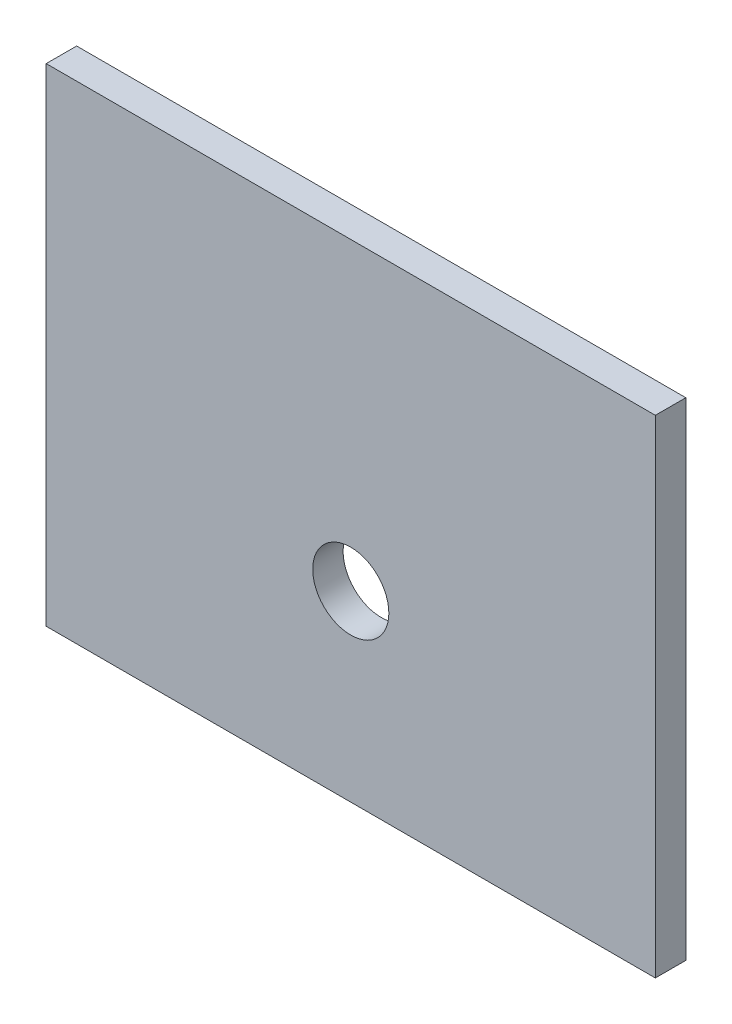
SolidWorks part; units mm, degrees
ref_plane "Front Plane" through (0, 0, 0) normal (0, 0, 1) x (1, 0, 0)
ref_plane "Top Plane" through (0, 0, 0) normal (0, 1, 0) x (1, 0, 0)
ref_plane "Right Plane" through (0, 0, 0) normal (1, 0, 0) x (0, 0, -1)
sketch "Sketch1" plane through (0, 0, 0) normal (0, 0, 1) x (1, 0, 0)
  line L1 (-31.75, 25.4) -> (31.75, 25.4)
  line L2 (-31.75, 25.4) -> (-31.75, -25.4)
  line L3 (-31.75, -25.4) -> (31.75, -25.4)
  line L4 (31.75, 25.4) -> (31.75, -25.4)
  line L5 (-31.75, 25.4) -> (31.75, -25.4) construction
  line L6 (-31.75, -25.4) -> (31.75, 25.4) construction
  circle A0 centre (0, -6.35) radius 3.9688
  point P0 (0, 0)
  dimension "D3" = 19.05
  dimension "D1" = 50.8
  dimension "D2" = 63.5
extrude "Boss-Extrude1" add sketch "Sketch1" along normal blind 3.175
sketch "Sketch2" plane through (0, 0, 3.175) normal (0, 0, 1) x (1, 0, 0)
